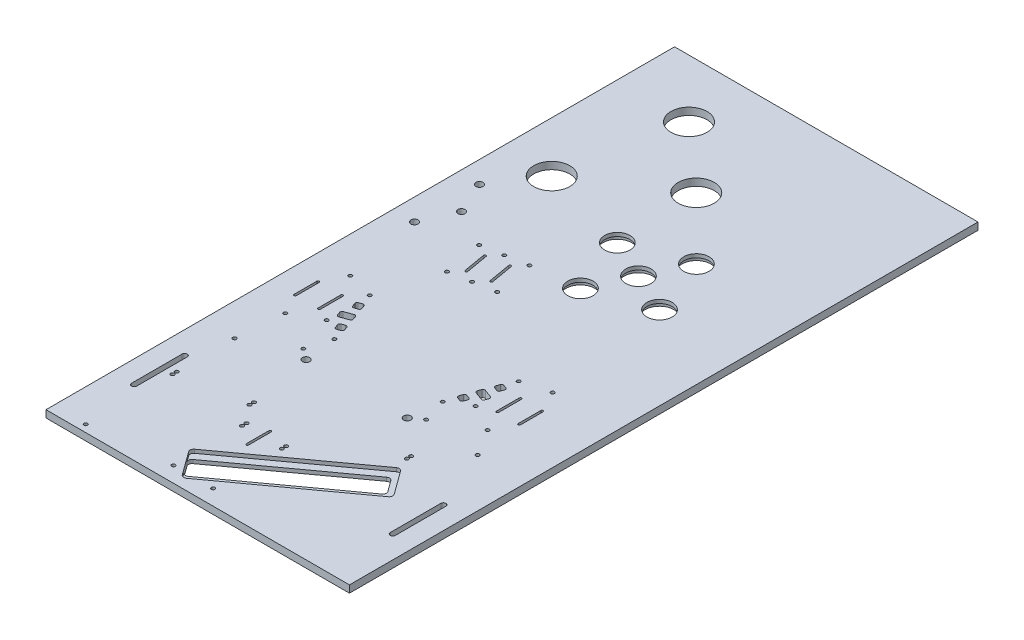
SolidWorks part; units mm, degrees
material "Pine"
ref_plane "Front Plane" through (0, 0, 0) normal (0, 0, 1) x (1, 0, 0)
ref_plane "Top Plane" through (0, 0, 0) normal (0, 1, 0) x (1, 0, 0)
ref_plane "Right Plane" through (0, 0, 0) normal (1, 0, 0) x (0, 0, -1)
sketch "Sketch1" plane through (0, 0, 0) normal (0, 1, 0) x (1, 0, 0)
  line L1 (0, 0) -> (533.4, 0)
  line L2 (0, 0) -> (0, 1104.9)
  line L3 (0, 1104.9) -> (533.4, 1104.9)
  line L4 (533.4, 0) -> (533.4, 1104.9)
  dimension "D1" = 533.4
  dimension "D2" = 1104.9
extrude "Boss-Extrude1" add sketch "Sketch1" along normal blind 12.7
hole_wizard "Launch system mounting holes" positions "Sketch4" profile "Sketch5" tap size "#8-32" standard "ANSI Inch"
sketch "Sketch4" plane through (0, 0, 0) normal (0, -1, 0) x (-1, 0, 0)
  line L0 (-533.4, 0) -> (-533.4, 1104.9) construction
  line L1 (0, 0) -> (-533.4, 0) construction
  point P0 (-509.905, 19.05)
  point P2 (-509.905, 63.5)
  point P4 (-509.905, 107.95)
  point P6 (-478.155, 107.95)
  point P8 (-478.155, 63.5)
  point P10 (-478.155, 19.8905)
  dimension "D1" = 23.495
  dimension "D2" = 23.495
  dimension "D3" = 23.495
  dimension "D4" = 19.05
  dimension "D5" = 44.45
  dimension "D6" = 44.45
  dimension "D7" = 31.75
  dimension "D8" = 0
  dimension "D9" = 0
  dimension "D10" = 31.75
  dimension "D11" = 31.75
sketch "Sketch5" plane through (509.905, 0, -19.05) normal (1, 0, 0) x (0, 0, -1)
  line L0 (0, 0) -> (0, 11.7058)
  line L1 (0, 11.7058) -> (1.7272, 10.668)
  line L2 (1.7272, 10.668) -> (1.7272, 0)
  line L5 (1.7272, 0) -> (0, 0)
  line L10 (0, 11.7058) -> (-1.7272, 10.668) construction
  line L11 (0, -6.35) -> (0, 107.95) construction
  dimension "Tap Drill Dia." = 3.4544
  dimension "Tap Drill Depth" = 10.668
  dimension "Drill Angle" = 118
sketch "Sketch6" plane through (0, 0, 0) normal (0, -1, 0) x (-1, 0, 0)
  line L0 (-494.03, 115.57) -> (-494.03, 204.47) construction
  line L1 (-498.475, 115.57) -> (-498.475, 204.47)
  line L2 (-489.585, 115.57) -> (-489.585, 204.47)
  line L3 (-533.4, 0) -> (-533.4, 1104.9) construction
  arc A0 (-498.475, 115.57) -> (-489.585, 115.57) centre (-494.03, 115.57) ccw
  arc A1 (-489.585, 204.47) -> (-498.475, 204.47) centre (-494.03, 204.47) ccw
  circle A3 centre (-509.905, 107.95) radius 1.7272 construction
  point P2 (-494.03, 160.02)
  dimension "D1" = 4.445
  dimension "D2" = 88.9
  dimension "D3" = 39.37
  dimension "D4" = 7.62
extrude "Cut-Extrude1" cut sketch "Sketch6" against normal through all
sketch "Sketch9" plane through (0, 12.7, 0) normal (0, 1, 0) x (1, 0, 0)
  line L0 (396.1251, 219.72) -> (190.6348, 70.4226)
  line L1 (189.23, 61.5529) -> (219.0895, 20.4548)
  line L2 (227.9592, 19.05) -> (433.4495, 168.3475)
  line L3 (434.8543, 177.2171) -> (404.9948, 218.3152)
  line L4 (0, 0) -> (533.4, 0) construction
  line L5 (0, 1104.9) -> (0, 0) construction
  arc A0 (433.4495, 168.3475) -> (434.8543, 177.2171) centre (429.7171, 173.4847) ccw
  arc A1 (396.1251, 219.72) -> (404.9948, 218.3152) centre (399.8576, 214.5828) cw
  arc A2 (190.6348, 70.4226) -> (189.23, 61.5529) centre (194.3673, 65.2853) ccw
  arc A3 (219.0895, 20.4548) -> (227.9592, 19.05) centre (224.2267, 24.1873) ccw
  point P6 (438.5868, 172.0799)
  point P11 (185.4976, 66.6901)
  point P14 (222.8219, 15.3176)
  dimension "D3" = 6.35
  dimension "D1" = 266.7
  dimension "D2" = 63.5
  dimension "D4" = 36
  dimension "D5" = 19.05
  dimension "D6" = 189.23
extrude "Cut-Extrude2" cut sketch "Sketch9" against normal blind 6.35
sketch "Sketch10" plane through (0, 6.35, 0) normal (0, 1, 0) x (1, 0, 0)
  line L0 (197.0681, 50.7646) -> (211.2514, 31.2431)
  line L1 (198.4729, 59.6343) -> (395.7436, 202.9599)
  line L2 (220.1211, 29.8382) -> (417.3918, 173.1638)
  line L3 (404.6133, 201.5551) -> (418.7966, 182.0335)
  line L4 (189.23, 61.5529) -> (219.0895, 20.4548) construction
  line L5 (227.9592, 19.05) -> (433.4495, 168.3475) construction
  arc A0 (211.2514, 31.2431) -> (220.1211, 29.8382) centre (216.3886, 34.9755) ccw
  arc A1 (198.4729, 59.6343) -> (197.0681, 50.7646) centre (202.2054, 54.4971) ccw
  arc A2 (417.3918, 173.1638) -> (418.7966, 182.0335) centre (413.6593, 178.3011) ccw
  arc A3 (395.7436, 202.9599) -> (404.6133, 201.5551) centre (399.4761, 197.8226) cw
  point P8 (214.9838, 26.1058)
  point P11 (193.3357, 55.9019)
  point P16 (400.8809, 206.6923)
  dimension "D2" = 6.35
  dimension "D1" = 256.54
  dimension "D3" = 36.83
  dimension "D4" = 13.335
extrude "Cut-Extrude3" cut sketch "Sketch10" against normal through all
sketch "Sketch11" plane through (0, 12.7, 0) normal (0, 1, 0) x (1, 0, 0)
  line L0 (533.4, 0) -> (533.4, 1104.9) construction
  line L1 (0, 0) -> (533.4, 0) construction
  circle A0 centre (152.4, 304.8) radius 6.35
  circle A1 centre (330.2, 304.8) radius 6.35
  dimension "D2" = 12.7
  dimension "D3" = 203.2
  dimension "D1" = 177.8
  dimension "D4" = 304.8
  dimension "D5" = 304.8
extrude "Cut-Extrude4" cut sketch "Sketch11" against normal through all
sketch "Sketch13" plane through (0, 12.7, 0) normal (0, 1, 0) x (1, 0, 0)
  line L0 (533.4, 1104.9) -> (0, 1104.9) construction
  line L1 (0, 1104.9) -> (0, 0) construction
  circle A0 centre (127, 1003.3) radius 31.75
  circle A1 centre (241.3, 901.7) radius 31.75
  circle A2 centre (88.9, 800.1) radius 31.75
  dimension "D1" = 63.5
  dimension "D2" = 101.6
  dimension "D3" = 127
  dimension "D4" = 203.2
  dimension "D5" = 241.3
  dimension "D6" = 304.8
  dimension "D7" = 88.9
extrude "Cut-Extrude5" cut sketch "Sketch13" against normal through all
sketch "Sketch14" plane through (0, 12.7, 0) normal (0, 1, 0) x (1, 0, 0)
  line L1 (142.0837, 381) -> (130.1496, 376.6563)
  line L2 (130.1496, 376.6563) -> (125.8059, 388.5904)
  line L3 (125.8059, 388.5904) -> (137.74, 392.9341)
  line L4 (129.0527, 416.8023) -> (133.3964, 404.8682)
  line L5 (133.3964, 404.8682) -> (113.1084, 397.484)
  line L6 (113.1084, 397.484) -> (108.7647, 409.4181)
  line L7 (108.7647, 409.4181) -> (129.0527, 416.8023)
  line L9 (124.7091, 428.7364) -> (112.775, 424.3927)
  line L10 (112.775, 424.3927) -> (108.4313, 436.3268)
  line L11 (108.4313, 436.3268) -> (120.3654, 440.6705)
  line L12 (120.3654, 440.6705) -> (124.7091, 428.7364)
  line L13 (137.74, 392.9341) -> (142.0837, 381)
  line L14 (241.3, 167.6639) -> (241.3, 453.0958) construction
  line L15 (374.1687, 436.3268) -> (362.2346, 440.6705)
  line L16 (369.825, 424.3927) -> (374.1687, 436.3268)
  line L17 (357.8909, 428.7364) -> (369.825, 424.3927)
  line L18 (362.2346, 440.6705) -> (357.8909, 428.7364)
  line L19 (353.5473, 416.8023) -> (349.2036, 404.8682)
  line L20 (373.8353, 409.4181) -> (353.5473, 416.8023)
  line L21 (369.4916, 397.484) -> (373.8353, 409.4181)
  line L22 (349.2036, 404.8682) -> (369.4916, 397.484)
  line L23 (344.86, 392.9341) -> (340.5163, 381)
  line L24 (356.7941, 388.5904) -> (344.86, 392.9341)
  line L25 (352.4504, 376.6563) -> (356.7941, 388.5904)
  line L26 (340.5163, 381) -> (352.4504, 376.6563)
  line L27 (0, 1104.9) -> (0, 0) construction
  line L28 (0, 0) -> (533.4, 0) construction
  circle A0 centre (152.4, 304.8) radius 6.35 construction
  circle A1 centre (146.05, 360.8195) radius 3.175
  circle A2 centre (110.432, 382.9948) radius 3.175
  circle A3 centre (110.432, 458.6791) radius 3.175
  circle A4 centre (372.168, 458.6791) radius 3.175
  circle A5 centre (372.168, 382.9948) radius 3.175
  circle A6 centre (336.55, 360.8195) radius 3.175
  point P0 (131.773, 390.7623)
  dimension "D7" = 88.9
  dimension "D11" = 6.35
  dimension "D1" = 12.7
  dimension "D2" = 12.7
  dimension "D3" = 12.7
  dimension "D4" = 21.59
  dimension "D5" = 12.7
  dimension "D6" = 12.7
  dimension "D8" = 20
  dimension "D9" = 6.35
  dimension "D10" = 381
  dimension "D12" = 20.32
  dimension "D13" = 20.32
  dimension "D14" = 3.175
  dimension "D15" = 3.175
  dimension "D16" = 0
  dimension "D17" = 12.7
extrude "Cut-Extrude6" cut sketch "Sketch14" against normal through all
fillet "Fillet1" radius 3.175 24 edges at (352.4504, 6.35, -376.6563) (340.5163, 6.35, -381) (356.7941, 6.35, -388.5904) (344.86, 6.35, -392.9341) (362.2346, 6.35, -440.6705) (374.1687, 6.35, -436.3268) (369.825, 6.35, -424.3927) (357.8909, 6.35, -428.7364) (353.5473, 6.35, -416.8023) (349.2036, 6.35, -404.8682) (369.4916, 6.35, -397.484) (373.8353, 6.35, -409.4181) (142.0837, 6.35, -381) (130.1496, 6.35, -376.6563) (137.74, 6.35, -392.9341) (125.8059, 6.35, -388.5904) (133.3964, 6.35, -404.8682) (113.1084, 6.35, -397.484) (129.0527, 6.35, -416.8023) (108.7647, 6.35, -409.4181) (124.7091, 6.35, -428.7364) (112.775, 6.35, -424.3927) (120.3654, 6.35, -440.6705) (108.4313, 6.35, -436.3268)
sketch "Sketch15" plane through (0, 12.7, 0) normal (0, 1, 0) x (1, 0, 0)
  line L0 (0, 1104.9) -> (0, 0) construction
  line L1 (241.3, 304.8) -> (241.3, 501.06) construction
  circle A0 centre (63.5, 471.3498) radius 3.175
  circle A1 centre (63.5, 357.0498) radius 3.175
  circle A2 centre (133.35, 318.9498) radius 3.175
  circle A3 centre (152.4, 304.8) radius 6.35 construction
  circle A4 centre (349.25, 318.9498) radius 3.175
  circle A5 centre (419.1, 471.3498) radius 3.175
  circle A6 centre (419.1, 357.0498) radius 3.175
  dimension "D2" = 6.35
  dimension "D1" = 152.4
  dimension "D3" = 63.5
  dimension "D4" = 63.5
  dimension "D5" = 19.05
  dimension "D6" = 114.3
  dimension "D7" = 88.9
extrude "Cut-Extrude7" cut sketch "Sketch15" against normal through all
ref_plane "Plane1" through (266.7, 0, 0) normal (-1, 0, 0) x (0, 0, 1)
mirror "Mirror1" about plane through (266.7, 0, 0) normal (-1, 0, 0) of "Cut-Extrude1", "Launch system mounting holes"
sketch "Sketch16" plane through (0, 12.7, 0) normal (0, 1, 0) x (1, 0, 0)
  line L0 (0, 1104.9) -> (0, 0) construction
  line L1 (0, 0) -> (533.4, 0) construction
  circle A0 centre (57.15, 12.7) radius 3.175
  circle A1 centre (57.15, 165.1) radius 3.175
  circle A2 centre (57.15, 172.72) radius 3.175
  circle A3 centre (57.15, 274.32) radius 3.175
  circle A4 centre (171.45, 193.9981) radius 3.175
  dimension "D1" = 6.35
  dimension "D2" = 6.35
  dimension "D4" = 57.15
  dimension "D7" = 6.35
  dimension "D9" = 7.62
  dimension "D10" = 6.35
  dimension "D12" = 6.35
  dimension "D3" = 57.15
  dimension "D5" = 152.4
  dimension "D6" = 12.7
  dimension "D8" = 57.15
  dimension "D11" = 101.6
  dimension "D13" = 139.7
  dimension "D14" = 114.3
extrude "Cut-Extrude8" cut sketch "Sketch16" against normal through all
sketch "Sketch17" plane through (0, 12.7, 0) normal (0, 1, 0) x (1, 0, 0)
  line L0 (0, 1104.9) -> (0, 0) construction
  circle A0 centre (196.85, 27.1978) radius 3.175
  circle A1 centre (266.7, 27.1978) radius 3.175
  circle A2 centre (266.7, 147.8478) radius 3.175
  circle A3 centre (196.85, 147.8478) radius 3.175
  dimension "D1" = 6.35
  dimension "D2" = 69.85
  dimension "D3" = 69.85
  dimension "D5" = 196.85
  dimension "D6" = 120.65
  dimension "D4" = 196.85
extrude "Cut-Extrude9" cut sketch "Sketch17" against normal through all
sketch "Sketch18" plane through (0, 12.7, 0) normal (0, 1, 0) x (1, 0, 0)
  circle A0 centre (171.45, 186.3781) radius 3.175
  circle A1 centre (196.85, 155.4678) radius 3.175
  circle A2 centre (171.45, 193.9981) radius 3.175 construction
  circle A3 centre (196.85, 147.8478) radius 3.175 construction
  dimension "D1" = 6.35
  dimension "D2" = 6.35
  dimension "D4" = 7.62
  dimension "D3" = 7.62
extrude "Cut-Extrude10" cut sketch "Sketch18" against normal through all
sketch "Sketch19" plane through (0, 12.7, 0) normal (0, 1, 0) x (1, 0, 0)
  circle A0 centre (266.7, 155.4678) radius 3.175
  circle A1 centre (391.709, 242.6372) radius 3.175
  circle A2 centre (266.7, 147.8478) radius 3.175 construction
  dimension "D1" = 6.35
  dimension "D2" = 6.35
  dimension "D4" = 7.62
  dimension "D3" = 152.4
extrude "Cut-Extrude11" cut sketch "Sketch19" against normal through all
sketch "Sketch20" plane through (0, 12.7, 0) normal (0, 1, 0) x (1, 0, 0)
  line L0 (533.4, 0) -> (533.4, 1104.9) construction
  circle A0 centre (391.709, 250.2572) radius 3.175
  circle A1 centre (391.709, 242.6372) radius 3.175 construction
  circle A2 centre (448.31, 310.3474) radius 3.175
  dimension "D1" = 6.35
  dimension "D2" = 7.62
  dimension "D3" = 6.35
  dimension "D4" = 85.09
  dimension "D5" = 82.55
extrude "Cut-Extrude12" cut sketch "Sketch20" against normal through all
sketch "Sketch21" plane through (0, 12.7, 0) normal (0, 1, 0) x (1, 0, 0)
  line L0 (0, 1104.9) -> (0, 0) construction
  line L1 (533.4, 1104.9) -> (0, 1104.9) construction
  circle A0 centre (38.1, 723.9) radius 6.35
  circle A1 centre (38.1, 609.6) radius 6.35
  circle A2 centre (63.5, 666.75) radius 6.35
  dimension "D1" = 12.7
  dimension "D2" = 114.3
  dimension "D3" = 25.4
  dimension "D4" = 57.15
  dimension "D5" = 38.1
  dimension "D6" = 381
extrude "Cut-Extrude13" cut sketch "Sketch21" against normal through all
sketch "Sketch22" plane through (0, 12.7, 0) normal (0, 1, 0) x (1, 0, 0)
  line L0 (387.0211, 691.4818) -> (285.0818, 654.3789) construction
  line L1 (285.0818, 654.3789) -> (247.9789, 756.3182) construction
  line L2 (247.9789, 756.3182) -> (349.9182, 793.4211) construction
  line L3 (349.9182, 793.4211) -> (387.0211, 691.4818) construction
  line L4 (533.4, 0) -> (533.4, 1104.9) construction
  line L5 (533.4, 1104.9) -> (0, 1104.9) construction
  circle A0 centre (317.5, 723.9) radius 22.225
  circle A1 centre (247.9789, 756.3182) radius 22.225
  circle A2 centre (285.0818, 654.3789) radius 22.225
  circle A3 centre (317.5, 723.9) radius 22.225
  circle A4 centre (387.0211, 691.4818) radius 22.225
  circle A5 centre (317.5, 723.9) radius 22.225
  circle A6 centre (349.9182, 793.4211) radius 22.225
  circle A7 centre (317.5, 723.9) radius 22.225
  point P16 (317.5, 723.9)
  dimension "D1" = 44.45
  dimension "D2" = 44.45
  dimension "D3" = 76.708
  dimension "D5" = 70
  dimension "D6" = 381
  dimension "D7" = 215.9
  dimension "D4" = 4
extrude "Cut-Extrude14" cut sketch "Sketch22" against normal through all contours A1 | A2 | A0 | A4 | A6
sketch "Sketch23" plane through (0, 0, 0) normal (0, -1, 0) x (-1, 0, 0)
  circle A0 centre (-317.5, 723.9) radius 25.4
  circle A1 centre (-349.9182, 793.4211) radius 25.4
  circle A2 centre (-247.9789, 756.3182) radius 25.4
  circle A3 centre (-285.0818, 654.3789) radius 25.4
  circle A4 centre (-387.0211, 691.4818) radius 25.4
  dimension "D1" = 50.8
extrude "Cut-Extrude15" cut sketch "Sketch23" against normal blind 6.35
sketch "Sketch24" plane through (0, 12.7, 0) normal (0, 1, 0) x (1, 0, 0)
  line L0 (229.87, 124.0728) -> (229.87, 164.0728) construction
  line L1 (227.87, 124.0728) -> (227.87, 164.0728)
  line L2 (231.87, 124.0728) -> (231.87, 164.0728)
  arc A0 (227.87, 124.0728) -> (231.87, 124.0728) centre (229.87, 124.0728) ccw
  arc A1 (231.87, 164.0728) -> (227.87, 164.0728) centre (229.87, 164.0728) ccw
  circle A2 centre (196.85, 147.8478) radius 3.175 construction
  point P2 (229.87, 144.0728)
  dimension "D2" = 2
  dimension "D1" = 40
  dimension "D3" = 33.02
extrude "Cut-Extrude16" cut sketch "Sketch24" against normal blind 22.098
sketch "Sketch25" plane through (0, 12.7, 0) normal (0, 1, 0) x (1, 0, 0)
  line L0 (44.45, 433.7) -> (44.45, 393.7) construction
  line L1 (46.45, 433.7) -> (46.45, 393.7)
  line L2 (42.45, 433.7) -> (42.45, 393.7)
  line L3 (0, 1104.9) -> (0, 0) construction
  line L4 (0, 0) -> (533.4, 0) construction
  arc A0 (46.45, 433.7) -> (42.45, 433.7) centre (44.45, 433.7) ccw
  arc A1 (42.45, 393.7) -> (46.45, 393.7) centre (44.45, 393.7) ccw
  point P2 (44.45, 413.7)
  dimension "D2" = 2
  dimension "D1" = 40
  dimension "D3" = 44.45
  dimension "D4" = 393.7
extrude "Cut-Extrude17" cut sketch "Sketch25" against normal through all
sketch "Sketch26" plane through (0, 12.7, 0) normal (0, 1, 0) x (1, 0, 0)
  line L0 (86.36, 433.7) -> (86.36, 393.7) construction
  line L1 (88.36, 433.7) -> (88.36, 393.7)
  line L2 (84.36, 433.7) -> (84.36, 393.7)
  line L3 (0, 0) -> (533.4, 0) construction
  line L4 (0, 1104.9) -> (0, 0) construction
  arc A0 (88.36, 433.7) -> (84.36, 433.7) centre (86.36, 433.7) ccw
  arc A1 (84.36, 393.7) -> (88.36, 393.7) centre (86.36, 393.7) ccw
  point P2 (86.36, 413.7)
  dimension "D2" = 2
  dimension "D1" = 40
  dimension "D3" = 393.7
  dimension "D4" = 86.36
extrude "Cut-Extrude18" cut sketch "Sketch26" against normal blind 72.136
sketch "Sketch27" plane through (0, 12.7, 0) normal (0, 1, 0) x (1, 0, 0)
  line L0 (438.15, 433.7) -> (438.15, 393.7) construction
  line L1 (440.15, 433.7) -> (440.15, 393.7)
  line L2 (436.15, 433.7) -> (436.15, 393.7)
  line L3 (400.05, 433.7) -> (400.05, 393.7) construction
  line L4 (402.05, 433.7) -> (402.05, 393.7)
  line L5 (398.05, 433.7) -> (398.05, 393.7)
  line L6 (0, 0) -> (533.4, 0) construction
  line L7 (533.4, 0) -> (533.4, 1104.9) construction
  arc A0 (440.15, 433.7) -> (436.15, 433.7) centre (438.15, 433.7) ccw
  arc A1 (436.15, 393.7) -> (440.15, 393.7) centre (438.15, 393.7) ccw
  arc A2 (402.05, 433.7) -> (398.05, 433.7) centre (400.05, 433.7) ccw
  arc A3 (398.05, 393.7) -> (402.05, 393.7) centre (400.05, 393.7) ccw
  point P2 (438.15, 413.7)
  point P7 (400.05, 413.7)
  dimension "D1" = 40
  dimension "D4" = 393.7
  dimension "D3" = 393.7
  dimension "D5" = 2
  dimension "D6" = 2
  dimension "D2" = 40
  dimension "D7" = 95.25
  dimension "D8" = 133.35
extrude "Cut-Extrude19" cut sketch "Sketch27" against normal blind 72.136
sketch "Sketch28" plane through (0, 12.7, 0) normal (0, 1, 0) x (1, 0, 0)
  line L0 (126.468, 633.8424) -> (207.7639, 648.177) construction
  line L1 (126.468, 633.8424) -> (139.7, 558.8) construction
  line L2 (207.7639, 648.177) -> (220.9959, 573.1347) construction
  line L3 (139.7, 558.8) -> (220.9959, 573.1347) construction
  line L4 (0, 1104.9) -> (0, 0) construction
  line L5 (0, 0) -> (533.4, 0) construction
  line L6 (151.4984, 619.8767) -> (158.4443, 580.4844) construction
  line L7 (153.468, 620.224) -> (160.4139, 580.8316)
  line L8 (149.5288, 619.5294) -> (156.4747, 580.1371)
  line L9 (189.0196, 626.4927) -> (195.9655, 587.1003) construction
  line L10 (190.9892, 626.84) -> (197.9351, 587.4476)
  line L11 (187.05, 626.1454) -> (193.9959, 586.7531)
  circle A0 centre (142.2754, 562.4781) radius 3.175
  circle A1 centre (130.1461, 631.2669) radius 3.175
  circle A2 centre (205.1885, 644.4989) radius 3.175
  circle A3 centre (217.3178, 575.7101) radius 3.175
  circle A4 centre (179.7966, 569.0941) radius 3.175
  circle A5 centre (167.6673, 637.8829) radius 3.175
  arc A6 (153.468, 620.224) -> (149.5288, 619.5294) centre (151.4984, 619.8767) ccw
  arc A7 (156.4747, 580.1371) -> (160.4139, 580.8316) centre (158.4443, 580.4844) ccw
  arc A8 (190.9892, 626.84) -> (187.05, 626.1454) centre (189.0196, 626.4927) ccw
  arc A9 (193.9959, 586.7531) -> (197.9351, 587.4476) centre (195.9655, 587.1003) ccw
  point P0 (133.084, 596.3212)
  point P23 (154.9714, 600.1805)
  point P28 (192.4925, 606.7965)
  dimension "D7" = 6.35
  dimension "D13" = 2
  dimension "D15" = 2
  dimension "D1" = 82.55
  dimension "D2" = 38.1
  dimension "D3" = 139.7
  dimension "D4" = 558.8
  dimension "D5" = 80
  dimension "D6" = 3.175
  dimension "D9" = 3.175
  dimension "D10" = 3.175
  dimension "D11" = 3.175
  dimension "D12" = 40
  dimension "D14" = 40
  dimension "D16" = 0
  dimension "D17" = 19.05
  dimension "D18" = 38.1
  dimension "D19" = 38.1
  dimension "D20" = 38.1
extrude "Cut-Extrude20" cut sketch "Sketch28" against normal blind 28.194
equation "\"L\"= 40mm"
equation "\"R\"= 2mm"
equation "\"D1@Sketch24\"=\"L\""
equation "\"D2@Sketch24\"=\"R\""
equation "\"D1@Sketch25\"=\"L\""
equation "\"D2@Sketch25\"=\"R\""
equation "\"D1@Sketch26\"=\"L\""
equation "\"D2@Sketch26\"=\"R\""
equation "\"D1@Sketch27\"=\"L\""
equation "\"D2@Sketch27\"=\"L\""
equation "\"D5@Sketch27\"=\"R\""
equation "\"D6@Sketch27\"=\"R\""
equation "\"D12@Sketch28\"=\"L\""
equation "\"D13@Sketch28\"=\"R\""
equation "\"D14@Sketch28\"=\"L\""
equation "\"D15@Sketch28\"=\"R\""
